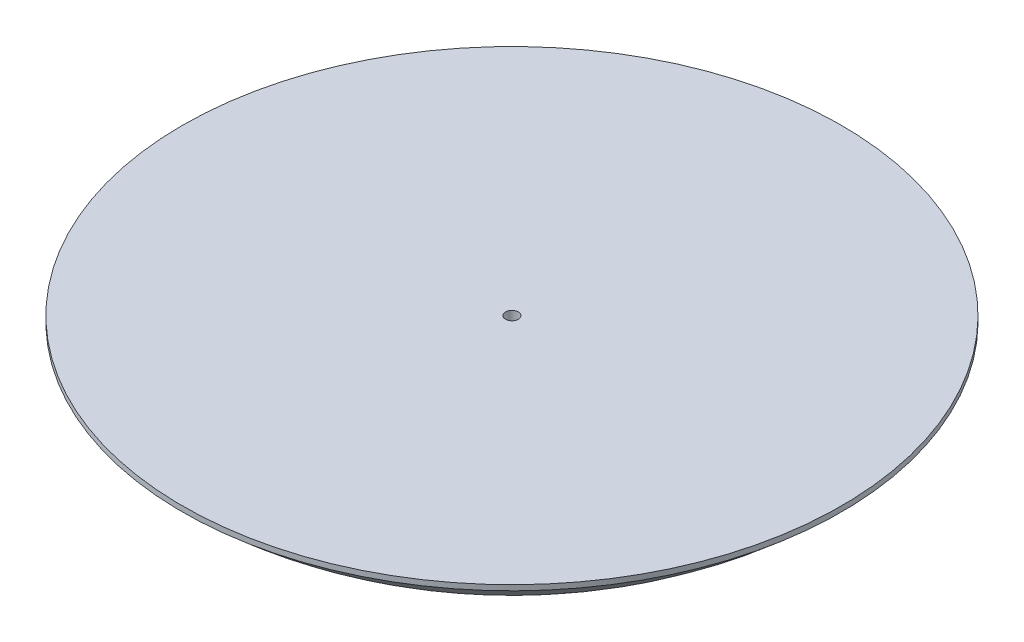
SolidWorks part; units mm, degrees
ref_plane "Front Plane" through (0, 0, 0) normal (0, 0, 1) x (1, 0, 0)
ref_plane "Top Plane" through (0, 0, 0) normal (0, 1, 0) x (1, 0, 0)
ref_plane "Right Plane" through (0, 0, 0) normal (1, 0, 0) x (0, 0, -1)
sketch "Sketch3" plane through (0, 0, 0) normal (0, 0, 1) x (1, 0, 0)
  line L0 (30, 18.317) -> (30, 35.1596) construction
  line L1 (30, 35.1596) -> (0, 35.1596) construction
  line L2 (0, 35.1596) -> (0, 0) construction
  line L4 (1.2, 35.1596) -> (1.2, 30.1596)
  line L5 (1.2, 30.1596) -> (0, 30.1596)
  line L6 (0, 30.1596) -> (0, 0)
  line L7 (30, 18.317) -> (33, 18.317) construction
  line L8 (33, 18.317) -> (33, 35.1596) construction
  line L10 (30, 18.317) -> (30, 19.317)
  line L11 (30, 19.317) -> (32, 19.317)
  line L12 (1.2, 35.1596) -> (62, 35.1596)
  line L13 (62, 35.1596) -> (62, 34.1596)
  spline S0 degree 8 poles (-2.8357, 1.3681) (1.6438, -4.2172) (6.1232, 6.4975) (10.6027, 4.0737) (15.0822, 10.3629) (19.5616, 12.0091) (24.0411, 14.9144) (28.5205, 17.5367) (33, 19.996) knots 0 0 0 0 0 0 0 0 0 1 1 1 1 1 1 1 1 1 construction
  spline S1 degree 8 poles (0, 0) (3.75, 0.2948) (7.5, 5.0483) (11.25, 6.1021) (15, 9.4337) (18.75, 11.7032) (22.5, 13.9531) (26.25, 16.1812) (30, 18.317) knots 0.07913 0.07913 0.07913 0.07913 0.07913 0.07913 0.07913 0.07913 0.07913 0.916285 0.916285 0.916285 0.916285 0.916285 0.916285 0.916285 0.916285 0.916285
  spline S2 degree 2 poles (29, 19.206) (46.7415, 19.1239) (64.483, 36.5069) knots 0 0 0 1 1 1 construction
  spline S3 degree 2 poles (32, 19.317) (47, 20.496) (62, 34.1596) knots 0.084547 0.084547 0.084547 0.930022 0.930022 0.930022
  point P12 (90.9008, 35.8367)
  point P15 (96.9539, 81.8959)
  point P19 (1039.3213, 2318.0214)
  point P21 (41.0011, 23.1737)
  point P22 (96.4474, 77.9283)
  point P23 (0, 0)
  point P24 (0, 0)
  point P25 (78.8686, 31.9508)
  point P26 (50.0887, 46.6592)
  point P27 (61.4599, 37.4905)
  dimension "D1" = 1
  dimension "D2" = 1.2
  dimension "D3" = 5
  dimension "D4" = 3
  dimension "D5" = 1
  dimension "D6" = 18.317
  dimension "D7" = 30
  dimension "D8" = 30
  dimension "D9" = 30
  dimension "D10" = 2
revolve "Revolve4" add sketch "Sketch3" angle 360 about L2
sketch "Sketch5" plane through (0, 35.1596, 0) normal (0, 1, 0) x (1, 0, 0)
  circle A0 centre (0, 0) radius 1.2
  circle A1 centre (0, 0) radius 1.2 construction
extrude "Cut-Extrude1" cut sketch "Sketch5" against normal through all
ref_plane "Plane1" through (0, 0.2672, 0) normal (0, -1, 0) x (-1, 0, 0)
sketch "Sketch6" plane through (0, 0.2672, 0) normal (0, -1, 0) x (-1, 0, 0)
  circle A0 centre (0, 0) radius 1.2 construction
  point P0 (0, 0)
